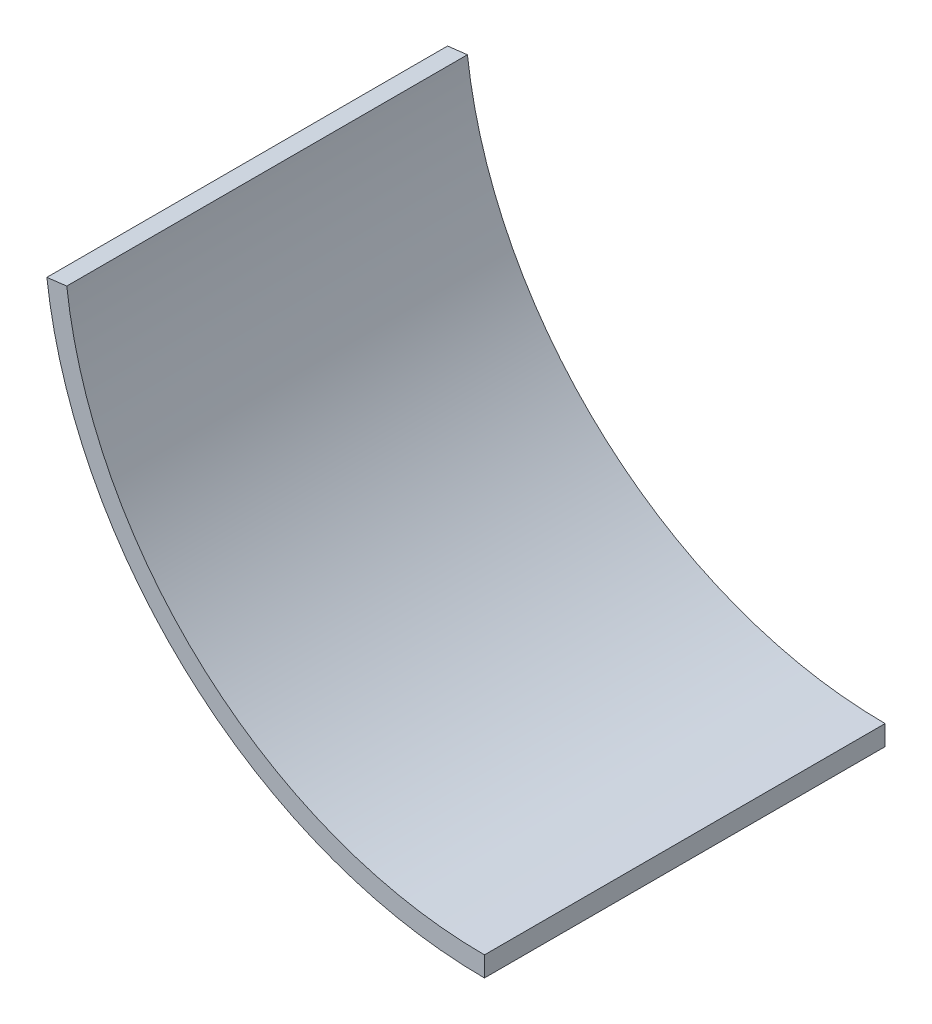
SolidWorks part; units mm, degrees
ref_plane "前基準面" through (0, 0, 0) normal (0, 0, 1) x (1, 0, 0)
ref_plane "上基準面" through (0, 0, 0) normal (0, 1, 0) x (1, 0, 0)
ref_plane "右基準面" through (0, 0, 0) normal (1, 0, 0) x (0, 0, -1)
sketch "草圖1" plane through (0, 0, 0) normal (0, 0, 1) x (1, 0, 0)
  line L0 (-170, -75) -> (-170, 75) construction
  line L1 (-170, -75) -> (60, -75) construction
  line L2 (-145, -56) -> (-145, -57)
  line L3 (-165.8491, -37.5128) -> (-166.8419, -37.6325)
  arc A0 (-145, -56) -> (-165.8491, -37.5128) centre (-145, -35) cw
  arc A1 (-145, -57) -> (-166.8419, -37.6325) centre (-145, -35) cw
  dimension "D1" = 21
  dimension "D2" = 25
  dimension "D3" = 40
  dimension "D4" = 1
extrude "填料-伸長1" add sketch "草圖1" along normal blind 20
